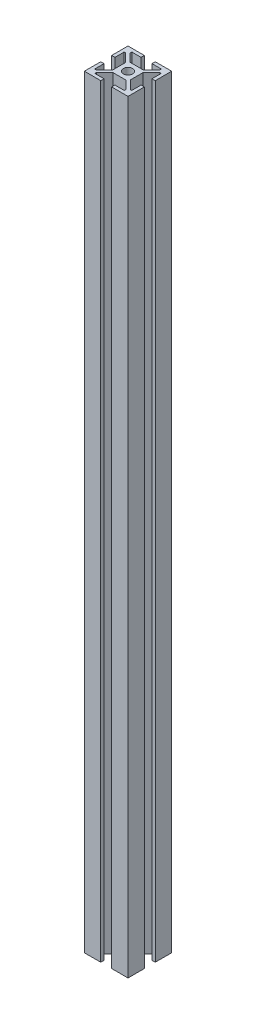
SolidWorks part; units mm, degrees
material "2024 Alloy"
ref_plane "Front Plane" through (0, 0, 0) normal (0, 0, 1) x (1, 0, 0)
ref_plane "Top Plane" through (0, 0, 0) normal (0, 1, 0) x (1, 0, 0)
ref_plane "Right Plane" through (0, 0, 0) normal (1, 0, 0) x (0, 0, -1)
sketch "Sketch1" plane through (0, 0, 0) normal (0, 1, 0) x (1, 0, 0)
  line L0 (-2.5, -993.4222) -> (-2.5, 49006.5778) construction
  line L1 (-10, 10) -> (-2.5, 10)
  line L2 (-10, 10) -> (-10, 2.5)
  line L3 (-10, -10) -> (-2.5, -10)
  line L4 (10, 10) -> (10, 2.5)
  line L5 (2.5, -994.5334) -> (2.5, 49005.4666) construction
  line L6 (-997.8427, 8.5) -> (49002.1573, 8.5) construction
  line L7 (-999.56, -8.5) -> (49000.44, -8.5) construction
  line L8 (8.5, -999.3828) -> (8.5, 49000.6172) construction
  line L9 (-2.9748, 4) -> (2.9748, 4)
  line L10 (-4, 2.9038) -> (-4, -2.9038)
  line L11 (-2.9748, -4) -> (2.9748, -4)
  line L12 (4, 2.9038) -> (4, -2.9038)
  line L13 (-8.5, -996.7327) -> (-8.5, 49003.2673) construction
  line L14 (2.5, 10) -> (2.5, 8.5)
  line L15 (2.5, 8.5) -> (6.75, 8.5)
  line L16 (8.5, 6.75) -> (8.5, 2.5)
  line L17 (8.5, 2.5) -> (10, 2.5)
  line L18 (-2.5, 10) -> (-2.5, 8.5)
  line L19 (-2.5, 8.5) -> (-6.75, 8.5)
  line L20 (-8.5, 6.75) -> (-8.5, 2.5)
  line L21 (-8.5, 2.5) -> (-10, 2.5)
  line L22 (-2.5, -10) -> (-2.5, -8.5)
  line L23 (-2.5, -8.5) -> (-6.75, -8.5)
  line L24 (-8.5, -6.75) -> (-8.5, -2.5)
  line L25 (-8.5, -2.5) -> (-10, -2.5)
  line L26 (2.5, -10) -> (2.5, -8.5)
  line L27 (2.5, -8.5) -> (6.75, -8.5)
  line L28 (8.5, -6.75) -> (8.5, -2.5)
  line L29 (8.5, -2.5) -> (10, -2.5)
  line L30 (2.5, 10) -> (10, 10)
  line L31 (-10, -2.5) -> (-10, -10)
  line L32 (10, -2.5) -> (10, -10)
  line L33 (0, 0) -> (35355.3391, 35355.3391) construction
  line L34 (2.9748, 4) -> (6.75, 7.7752)
  line L35 (4, 2.9038) -> (7.8462, 6.75)
  line L36 (-1012.3135, 6.75) -> (48987.6865, 6.75) construction
  line L37 (7.8462, 6.75) -> (8.5, 6.75)
  line L38 (6.75, -989.0284) -> (6.75, 49010.9716) construction
  line L39 (6.75, 7.7752) -> (6.75, 8.5)
  line L40 (0, -1000) -> (0, 49000) construction
  line L41 (-1000, 0) -> (49000, 0) construction
  line L42 (-6.75, 7.7752) -> (-6.75, 8.5)
  line L43 (-7.8462, 6.75) -> (-8.5, 6.75)
  line L44 (-2.9748, 4) -> (-6.75, 7.7752)
  line L45 (-4, 2.9038) -> (-7.8462, 6.75)
  line L46 (6.75, -7.7752) -> (6.75, -8.5)
  line L47 (7.8462, -6.75) -> (8.5, -6.75)
  line L48 (4, -2.9038) -> (7.8462, -6.75)
  line L49 (2.9748, -4) -> (6.75, -7.7752)
  line L50 (-2.9748, -4) -> (-6.75, -7.7752)
  line L51 (-6.75, -7.7752) -> (-6.75, -8.5)
  line L52 (-7.8462, -6.75) -> (-8.5, -6.75)
  line L53 (-4, -2.9038) -> (-7.8462, -6.75)
  line L54 (2.5, -10) -> (10, -10)
  circle A0 centre (0, 0) radius 2.15
  dimension "D7" = 4.3
  dimension "D1" = 20
  dimension "D2" = 20
  dimension "D3" = 10
  dimension "D4" = 10
  dimension "D5" = 7.5
  dimension "D6" = 7.5
  dimension "D9" = 4
  dimension "D10" = 4
  dimension "D11" = 1.5
  dimension "D13" = 7.5
  dimension "D15" = 7.5
  dimension "D16" = 1.5
  dimension "D17" = 7.5
  dimension "D18" = 7.5
  dimension "D19" = 1.5
  dimension "D20" = 3.25
  dimension "D21" = 3.25
extrude "Boss-Extrude1" add sketch "Sketch1" along normal blind 350
